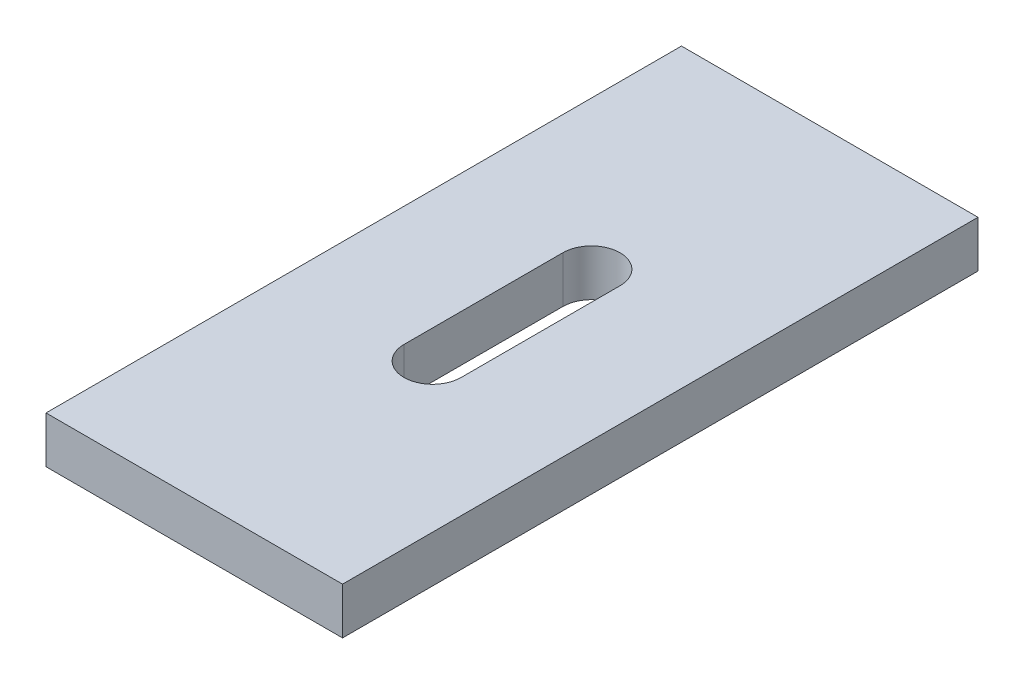
SolidWorks part; units mm, degrees
ref_plane "Front Plane" through (0, 0, 0) normal (0, 0, 1) x (1, 0, 0)
ref_plane "Top Plane" through (0, 0, 0) normal (0, 1, 0) x (1, 0, 0)
ref_plane "Right Plane" through (0, 0, 0) normal (1, 0, 0) x (0, 0, -1)
sketch "Sketch1" plane through (0, 0, 0) normal (0, 0, 1) x (1, 0, 0)
  line L1 (8.89, 1.397) -> (-8.89, 1.397)
  line L2 (8.89, 1.397) -> (8.89, -1.397)
  line L3 (8.89, -1.397) -> (-8.89, -1.397)
  line L4 (-8.89, 1.397) -> (-8.89, -1.397)
  line L5 (8.89, 1.397) -> (-8.89, -1.397) construction
  line L6 (8.89, -1.397) -> (-8.89, 1.397) construction
  point P0 (0, 0)
  dimension "D1" = 2.794
  dimension "D2" = 17.78
extrude "Boss-Extrude1" add sketch "Sketch1" along normal mid plane 38.1
sketch "Sketch2" plane through (0, 1.397, 0) normal (0, 1, 0) x (1, 0, 0)
  line L0 (0, 0) -> (0, -50000) construction
  line L1 (0, -4.7625) -> (0, 4.7625) construction
  line L2 (-1.7145, -4.7625) -> (-1.7145, 4.7625)
  line L3 (1.7145, -4.7625) -> (1.7145, 4.7625)
  arc A0 (-1.7145, -4.7625) -> (1.7145, -4.7625) centre (0, -4.7625) ccw
  arc A1 (1.7145, 4.7625) -> (-1.7145, 4.7625) centre (0, 4.7625) ccw
  point P5 (0, 0)
  point P10 (0, 0)
  dimension "D1" = 1.7145
  dimension "D2" = 9.525
extrude "Cut-Extrude1" cut sketch "Sketch2" against normal through all
